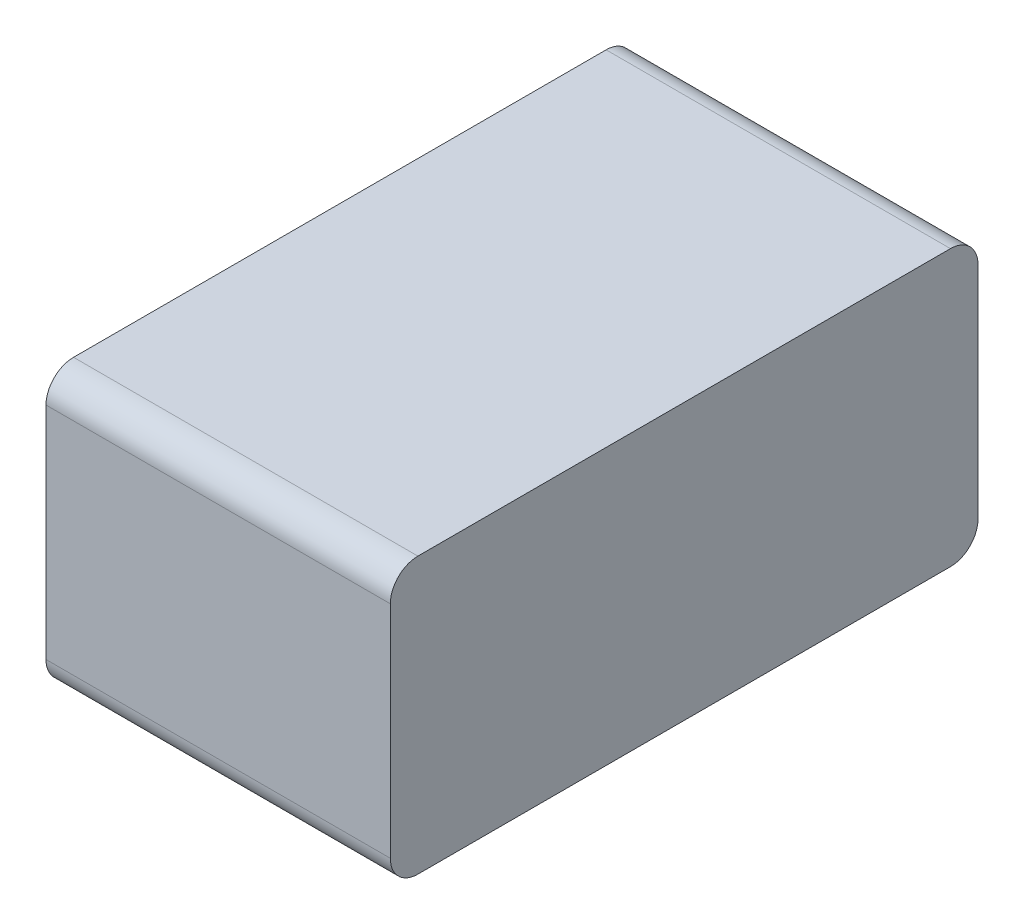
SolidWorks part; units mm, degrees
ref_plane "Front Plane" through (0, 0, 0) normal (1, 0, 0) x (0, 1, 0)
ref_plane "Top Plane" through (0, 0, 0) normal (0, 0, 1) x (0, 1, 0)
ref_plane "Right Plane" through (0, 0, 0) normal (0, 1, 0) x (-1, 0, 0)
sketch "Sketch1" plane through (0, 0, 0) normal (1, 0, 0) x (0, 1, 0)
  line L0 (-15, -32) -> (15, -32)
  line L1 (15, -32) -> (15, 32)
  line L2 (15, 32) -> (-15, 32)
  line L3 (-15, 32) -> (-15, -32)
extrude "Block" add sketch "Sketch1" along normal blind 37.5
fillet "BlockFillet" radius 3 4 edges at (18.75, -15, 32) (18.75, 15, 32) (18.75, 15, -32) (18.75, -15, -32)
sketch "Sketch2" plane through (0, 0, 0) normal (-1, 0, 0) x (0, -1, 0)
  circle A0 centre (-3, -20) radius 5.5
  circle A1 centre (-3, 0) radius 5.5
  circle A2 centre (-3, 20) radius 5.5
extrude "JackHoles" cut sketch "Sketch2" against normal blind 36.5
